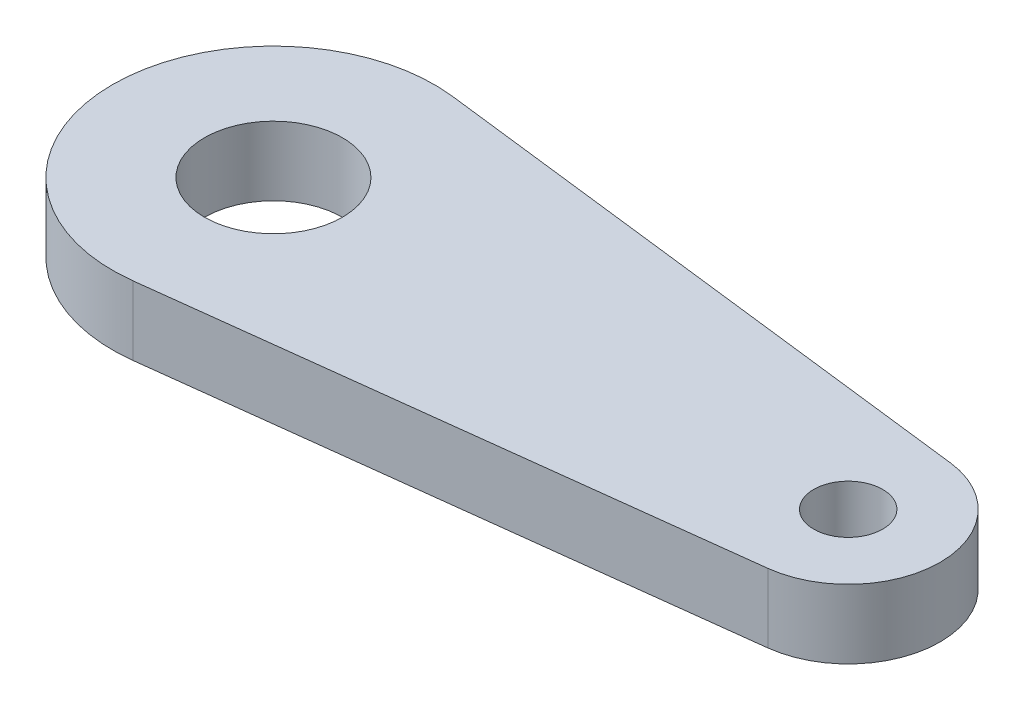
SolidWorks part; units mm, degrees
ref_plane "Front Plane" through (0, 0, 0) normal (0, 0, 1) x (1, 0, 0)
ref_plane "Top Plane" through (0, 0, 0) normal (0, 1, 0) x (1, 0, 0)
ref_plane "Right Plane" through (0, 0, 0) normal (1, 0, 0) x (0, 0, -1)
sketch "Sketch1" plane through (0, 0, 0) normal (0, 1, 0) x (1, 0, 0)
  line L0 (25.48, 3.9711) -> (0.84, 6.9494)
  line L1 (25.48, -3.9711) -> (0.84, -6.9494)
  line L2 (0, 0) -> (25, 0) construction
  circle A0 centre (0, 0) radius 3
  circle A1 centre (25, 0) radius 1.5
  arc A2 (0.84, 6.9494) -> (0.84, -6.9494) centre (0, 0) ccw
  arc A3 (25.48, -3.9711) -> (25.48, 3.9711) centre (25, 0) ccw
  dimension "D1" = 7
  dimension "D2" = 4
  dimension "D3" = 6
  dimension "D4" = 3
  dimension "D5" = 25
extrude "Boss-Extrude1" add sketch "Sketch1" along normal blind 3
